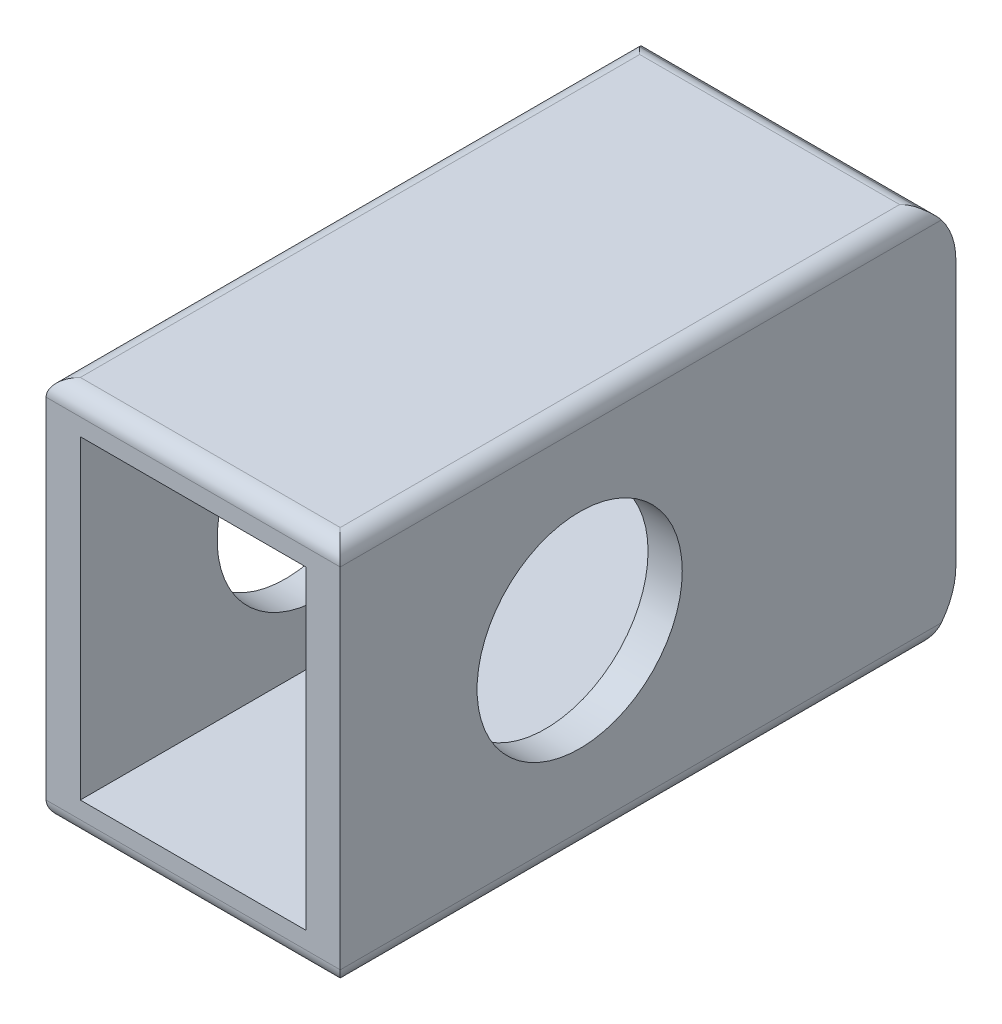
SolidWorks part; units mm, degrees
ref_plane "Plan de face" through (0, 0, 0) normal (0, 0, 1) x (1, 0, 0)
ref_plane "Plan de dessus" through (0, 0, 0) normal (0, 1, 0) x (1, 0, 0)
ref_plane "Plan de droite" through (0, 0, 0) normal (1, 0, 0) x (0, 0, -1)
sketch "Esquisse1" plane through (0, 0, 0) normal (0, 0, 1) x (1, 0, 0)
  line L0 (-4.7681, -7.2637) -> (3.8319, -7.2637)
  line L5 (-4.7681, -7.2637) -> (-4.7681, 3.9363)
  line L6 (-4.7681, 3.9363) -> (3.8319, 3.9363)
  line L7 (3.8319, -7.2637) -> (3.8319, 3.9363)
  dimension "D1" = 8.6
  dimension "D2" = 11.2
extrude "Boss.-Extru.1" add sketch "Esquisse1" along normal blind 18
shell "Coque1" thickness 1
sketch "Esquisse2" plane through (3.8319, 0, 0) normal (1, 0, 0) x (0, 0, -1)
  line L0 (0, -7.2637) -> (0, 3.9363) construction
  line L1 (0, -7.2637) -> (0, 3.9363)
  line L2 (-18, 3.9363) -> (0, 3.9363) construction
  line L3 (-1, 3.9363) -> (0, 3.9363)
  line L4 (0, -7.2637) -> (0, 3.9363)
  line L5 (0, 3.9363) -> (-18, 3.9363)
  line L6 (-18, 3.9363) -> (-18, -7.2637)
  line L7 (-18, -7.2637) -> (0, -7.2637)
  line L8 (0, -5.5317) -> (0, 2.2042)
  line L12 (-18, -7.2637) -> (0, -7.2637) construction
  line L13 (-1, -7.2637) -> (0, -7.2637)
  line L14 (-19.2108, -1.6637) -> (11.7071, -1.6637) construction
  arc A0 (0, -5.5317) -> (-1, -7.2637) centre (-2, -5.5317) cw
  arc A1 (0, 2.2042) -> (-1, 3.9363) centre (-2, 2.2042) ccw
  circle A2 centre (-11, -1.6637) radius 3
  line M7 (0, -7.2637) -> (0, 3.9363)
  line M8 (0, 3.9363) -> (-18, 3.9363)
  line M10 (-18, -7.2637) -> (0, -7.2637)
  dimension "D2" = 2
  dimension "D3" = 6
  dimension "D4" = 11
  dimension "D1" = 0
extrude "Enlèv. mat.-Extru.1" cut sketch "Esquisse2" against normal blind 20 contours A1 M7 M8 | A0 M7 M10 | A2
fillet "Congé2" radius 0.5 8 edges at (-0.4681, -7.2637, 18) (3.8319, -7.2637, 9.5) (-0.4681, -7.2637, 1) (-4.7681, -7.2637, 9.5) (3.8319, 3.9363, 9.5) (-0.4681, 3.9363, 18) (-4.7681, 3.9363, 9.5) (-0.4681, 3.9363, 1)
